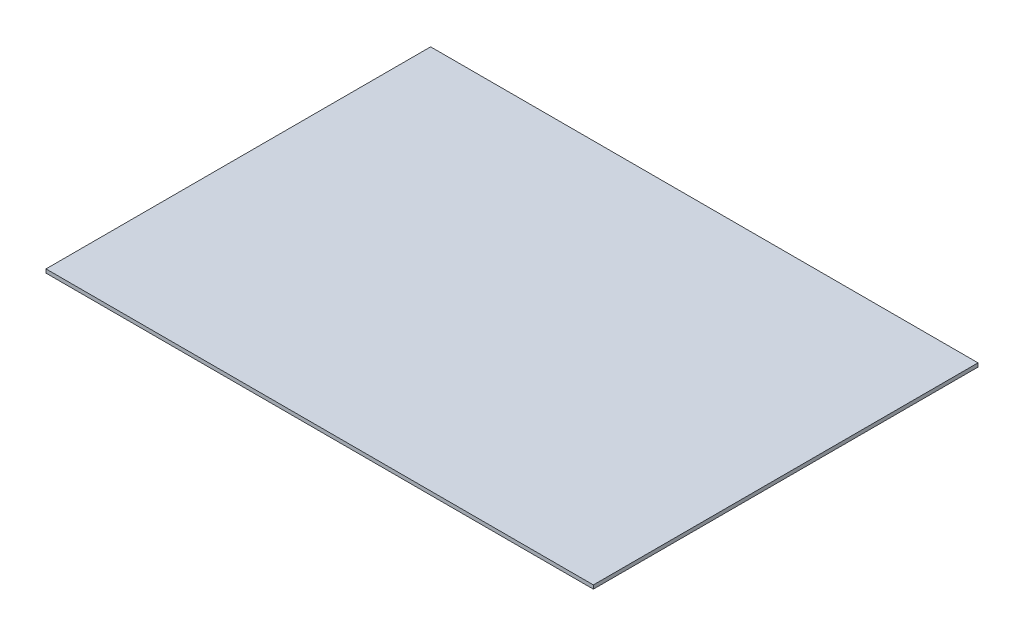
SolidWorks part; units mm, degrees
material "6061 Alloy"
ref_plane "Front Plane" through (0, 0, 0) normal (0, 0, 1) x (1, 0, 0)
ref_plane "Top Plane" through (0, 0, 0) normal (0, 1, 0) x (1, 0, 0)
ref_plane "Right Plane" through (0, 0, 0) normal (1, 0, 0) x (0, 0, -1)
sketch "Sketch2" plane through (0, 0, 0) normal (0, 1, 0) x (1, 0, 0)
  line L1 (-117.475, 82.55) -> (117.475, 82.55)
  line L2 (-117.475, 82.55) -> (-117.475, -82.55)
  line L3 (-117.475, -82.55) -> (117.475, -82.55)
  line L4 (117.475, 82.55) -> (117.475, -82.55)
  line L5 (-117.475, 82.55) -> (117.475, -82.55) construction
  line L6 (-117.475, -82.55) -> (117.475, 82.55) construction
  point P0 (0, 0)
  dimension "D1" = 165.1
  dimension "D2" = 234.95
extrude "Boss-Extrude1" add sketch "Sketch2" along normal mid plane 1.5875
